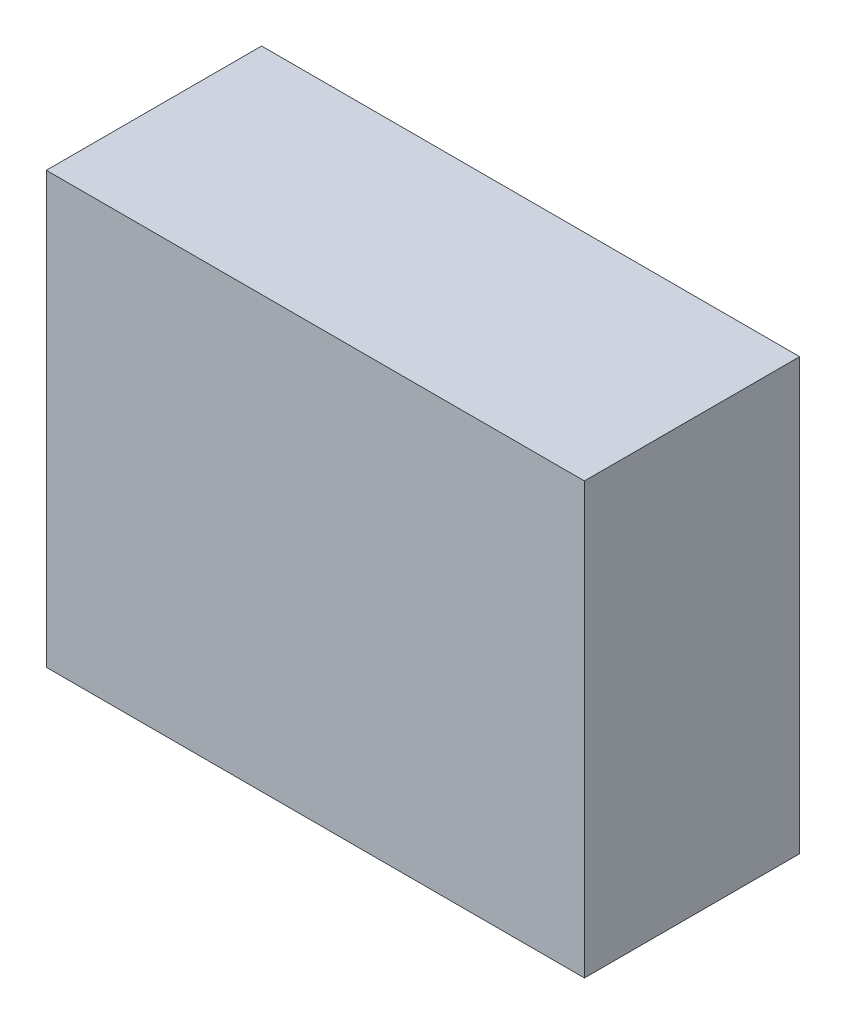
SolidWorks part; units mm, degrees
ref_plane "Front Plane" through (0, 0, 0) normal (0, 0, 1) x (1, 0, 0)
ref_plane "Top Plane" through (0, 0, 0) normal (0, 1, 0) x (1, 0, 0)
ref_plane "Right Plane" through (0, 0, 0) normal (1, 0, 0) x (0, 0, -1)
sketch "Sketch1" plane through (0, 0, 0) normal (0, 0, 1) x (1, 0, 0)
  line L1 (0, 0) -> (25, 0)
  line L2 (0, 0) -> (0, 20)
  line L3 (0, 20) -> (25, 20)
  line L4 (25, 0) -> (25, 20)
extrude "Boss-Extrude1" add sketch "Sketch1" along normal blind 10
